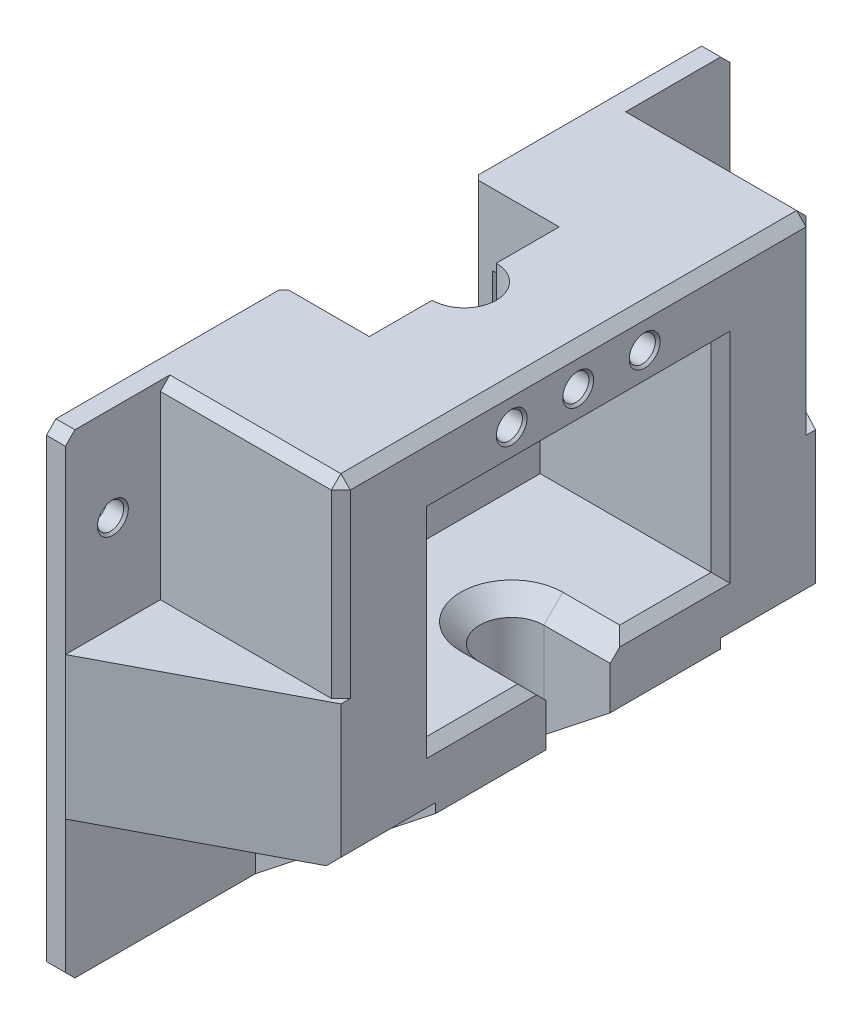
SolidWorks part; units mm, degrees
ref_plane "前视基准面" through (0, 0, 0) normal (0, 0, 1) x (1, 0, 0)
ref_plane "上视基准面" through (0, 0, 0) normal (0, 1, 0) x (1, 0, 0)
ref_plane "右视基准面" through (0, 0, 0) normal (1, 0, 0) x (0, 0, -1)
sketch "草图1" plane through (0, 0, 0) normal (1, 0, 0) x (0, 0, -1)
  line L1 (-70, 40) -> (70, 40)
  line L2 (-70, 40) -> (-70, -60)
  line L3 (-70, -60) -> (70, -60)
  line L4 (70, 40) -> (70, -60)
  dimension "D1" = 100
  dimension "D2" = 140
  dimension "D3" = 70
  dimension "D4" = 40
extrude "凸台-拉伸1" add sketch "草图1" along normal blind 4
sketch "草图9" plane through (4, 0, 0) normal (1, 0, 0) x (0, 0, -1)
  line L0 (70, -60) -> (70, 40) construction
  line L1 (-60, 20) -> (60, 20) construction
  line L2 (-60, 20) -> (-60, -40) construction
  line L3 (-60, -40) -> (60, -40) construction
  line L4 (60, 20) -> (60, -40) construction
  line L5 (70, 40) -> (-70, 40) construction
  circle A0 centre (-60, 20) radius 2.75
  circle A2 centre (60, 20) radius 2.75
  circle A4 centre (-45, -40) radius 2.75
  circle A5 centre (45, -40) radius 2.75
  dimension "D5" = 5.5
  dimension "D6" = 5.5
  dimension "D7" = 45
  dimension "D1" = 60
  dimension "D2" = 120
  dimension "D3" = 10
  dimension "D4" = 20
  dimension "D8" = 45
extrude "切除-拉伸3" cut sketch "草图9" against normal blind 8
chamfer "倒角2" distance 2 angle 45 4 edges at (2, -60, -70) (2, 40, -70) (2, 40, 70) (2, -60, 70)
sketch "草图11" plane through (4, 0, 0) normal (1, 0, 0) x (0, 0, -1)
  line L0 (68, 40) -> (-68, 40) construction
  line L1 (-20, 40) -> (20, 40)
  line L2 (-20, 40) -> (-20, -10)
  line L3 (-20, -10) -> (20, -10)
  line L4 (20, 40) -> (20, -10)
  dimension "D1" = 20
  dimension "D2" = 20
  dimension "D3" = 10
extrude "切除-拉伸5" cut sketch "草图11" against normal blind 5
sketch "草图12" plane through (4, 0, 0) normal (1, 0, 0) x (0, 0, -1)
  line L1 (-20, 40) -> (-30, 40)
  line L2 (-20, 40) -> (-20, 25)
  line L3 (-20, 25) -> (-30, 25)
  line L4 (-30, 40) -> (-30, 25)
  line L5 (20, 40) -> (30, 40)
  line L6 (20, 40) -> (20, 25)
  line L7 (20, 25) -> (30, 25)
  line L8 (30, 40) -> (30, 25)
  dimension "D1" = 10
  dimension "D2" = 10
  dimension "D3" = 15
  dimension "D4" = 15
extrude "凸台-拉伸2" add sketch "草图12" along normal blind 14
sketch "草图13" plane through (18, 0, 0) normal (1, 0, 0) x (0, 0, -1)
  line L1 (-30, 40) -> (30, 40)
  line L2 (-30, 40) -> (-30, 25)
  line L3 (-30, 25) -> (30, 25)
  line L4 (30, 40) -> (30, 25)
extrude "凸台-拉伸3" add sketch "草图13" along normal blind 14
sketch "草图14" plane through (0, 0, 30) normal (0, 0, 1) x (1, 0, 0)
  line L0 (4, 40) -> (4, -30)
  line L3 (32, -30) -> (32, 40)
  line L4 (32, 40) -> (4, 40)
  line L6 (32, -30) -> (4, -30)
  line L7 (4, 38) -> (4, -58) construction
  dimension "D1" = 70
extrude "凸台-拉伸4" add sketch "草图14" along normal blind 20
sketch "草图15" plane through (0, 0, -30) normal (0, 0, -1) x (-1, 0, 0)
  line L4 (-4, 40) -> (-32, 40)
  line L5 (-4, -30) -> (-4, 40)
  line L6 (-32, -30) -> (-4, -30)
  line L7 (-32, 40) -> (-32, -30)
  line L8 (-4, 40) -> (-32, 40)
  line L9 (-4, -30) -> (-4, 40)
  line L11 (-32, 40) -> (-32, -30)
  line L12 (-32, -30) -> (-4, -30)
  dimension "D1" = 0
extrude "凸台-拉伸5" add sketch "草图15" along normal blind 20
sketch "草图16" plane through (0, 40, 0) normal (0, 1, 0) x (1, 0, 0)
  line L0 (18, 20) -> (18, -20) construction
  circle A0 centre (18, 0) radius 6.75
  dimension "D1" = 13.5
extrude "切除-拉伸6" cut sketch "草图16" against normal blind 20
sketch "草图17" plane through (32, 0, 0) normal (1, 0, 0) x (0, 0, -1)
  line L6 (50, 40) -> (-50, 40)
  line L7 (-50, 40) -> (-50, -30)
  line L8 (-50, -30) -> (-30, -30)
  line L9 (-30, 25) -> (30, 25)
  line L10 (30, -30) -> (50, -30)
  line L11 (50, -30) -> (50, 40)
  line L12 (50, 40) -> (-50, 40)
  line L13 (-50, 40) -> (-50, -30)
  line L15 (-30, 25) -> (30, 25)
  line L16 (30, -30) -> (50, -30)
  line L17 (50, -30) -> (50, 40)
  line L20 (-50, -30) -> (-30, -30)
  line L21 (-30, -30) -> (-30, 25)
  line L22 (-30, -30) -> (-30, 25)
  line L23 (30, 25) -> (30, -30)
  line L24 (30, 25) -> (30, -30)
  dimension "D1" = 0
extrude "凸台-拉伸6" add sketch "草图17" along normal blind 10
sketch "草图18" plane through (18, 0, 0) normal (-1, 0, 0) x (0, 0, 1)
  line L0 (6.75, 40) -> (20, 40) construction
  line L1 (-20, 40) -> (-6.75, 40) construction
  circle A0 centre (14, 32.5) radius 2.75
  circle A1 centre (-14, 32.5) radius 2.75
  dimension "D1" = 5.5
  dimension "D2" = 5.5
  dimension "D3" = 28
  dimension "D4" = 14
  dimension "D5" = 7.5
  dimension "D6" = 7.5
extrude "切除-拉伸7" cut sketch "草图18" against normal through all
sketch "草图19" plane through (42, 0, 0) normal (1, 0, 0) x (0, 0, -1)
  circle A0 centre (0, 32.5) radius 2.75
  dimension "D1" = 5.5
  dimension "D2" = 32.5
extrude "切除-拉伸8" cut sketch "草图19" against normal blind 100
chamfer "倒角3" distance 0.5 angle 45 4 edges at (4, -40, 42.25) (4, -40, -47.75) (4, 20, -62.75) (4, 20, 57.25)
sketch "草图20" plane through (0, 0, 50) normal (0, 0, 1) x (1, 0, 0)
  line L0 (42, 25) -> (4, -30)
  line L1 (4, -30) -> (32, 25)
  line L2 (32, 25) -> (42, 25)
  line L5 (42, 40) -> (42, -30) construction
  dimension "D1" = 10
  dimension "D2" = 32
  dimension "D3" = 25
  dimension "D4" = 30
  dimension "D5" = 38
extrude "凸台-拉伸7" add sketch "草图20" against normal blind 20
sketch "草图21" plane through (0, 0, -50) normal (0, 0, -1) x (-1, 0, 0)
  line L0 (-42, 25) -> (-4, -30)
  line L1 (-4, -30) -> (-32, 25)
  line L2 (-32, 25) -> (-42, 25)
  dimension "D1" = 10
  dimension "D2" = 32
  dimension "D3" = 25
extrude "凸台-拉伸8" add sketch "草图21" against normal blind 20
sketch "草图22" plane through (0, 0, -30) normal (0, 0, 1) x (1, 0, 0)
  line L0 (42, -17) -> (4, -17)
  line L1 (42, 25) -> (42, -30) construction
  line L2 (4, -30) -> (4, 25) construction
  line L3 (4, -17) -> (4, -60)
  line L5 (42, 25) -> (4, 25) construction
  line L6 (42, -17) -> (42, -30)
  line L7 (42, -30) -> (4, -60)
  dimension "D1" = 42
extrude "凸台-拉伸9" add sketch "草图22" along normal up to surface (60 mm away) up to face at (23, -2.5, 30)
sketch "草图23" plane through (0, -30, 0) normal (0, -1, 0) x (1, 0, 0)
  line L0 (42, 50) -> (4, 70)
  line L1 (4, 70) -> (4, 50)
  line L2 (4, 50) -> (42, 50)
extrude "凸台-拉伸10" add sketch "草图23" against normal blind 30
mirror "镜向1" about plane through (0, 0, 0) normal (0, 0, 1) of "凸台-拉伸10"
chamfer "倒角4" distance 0.5 angle 45 3 edges at (42, 32.5, -11.25) (42, 32.5, -2.75) (42, 32.5, 16.75)
chamfer "倒角5" distance 2 angle 45 4 edges at (42, -17, 0) (42, 4, 30) (42, 25, 0) (42, 4, -30)
chamfer "倒角6" distance 2 angle 45 7 edges at (42, -30, 40) (42, -30, -40) (42, 20, 50) (42, 20, -50) (23, 40, -50) (42, 40, 0) (23, 40, 50)
chamfer "倒角7" distance 1 angle 45 3 edges at (0, 15, 20) (0, -10, 0) (0, 15, -20)
sketch "草图24" plane through (0, -17, 0) normal (0, 1, 0) x (1, 0, 0)
  line L1 (42, 32) -> (42, -32) construction
  line L2 (28, 6.75) -> (43.6691, 6.75)
  line L3 (43.6691, 6.75) -> (43.6691, -6.75)
  line L4 (43.6691, -6.75) -> (28, -6.75)
  line L5 (40, -30) -> (40, 30) construction
  arc A0 (28, 6.75) -> (28, -6.75) centre (28, 0) ccw
  point P11 (40, 0)
  dimension "D1" = 13.5
  dimension "D2" = 14
extrude "切除-拉伸9" cut sketch "草图24" against normal through all
chamfer "倒角8" distance 4 angle 45 3 edges at (34, -17, -6.75) (34, -17, 6.75) (21.25, -17, 0)
